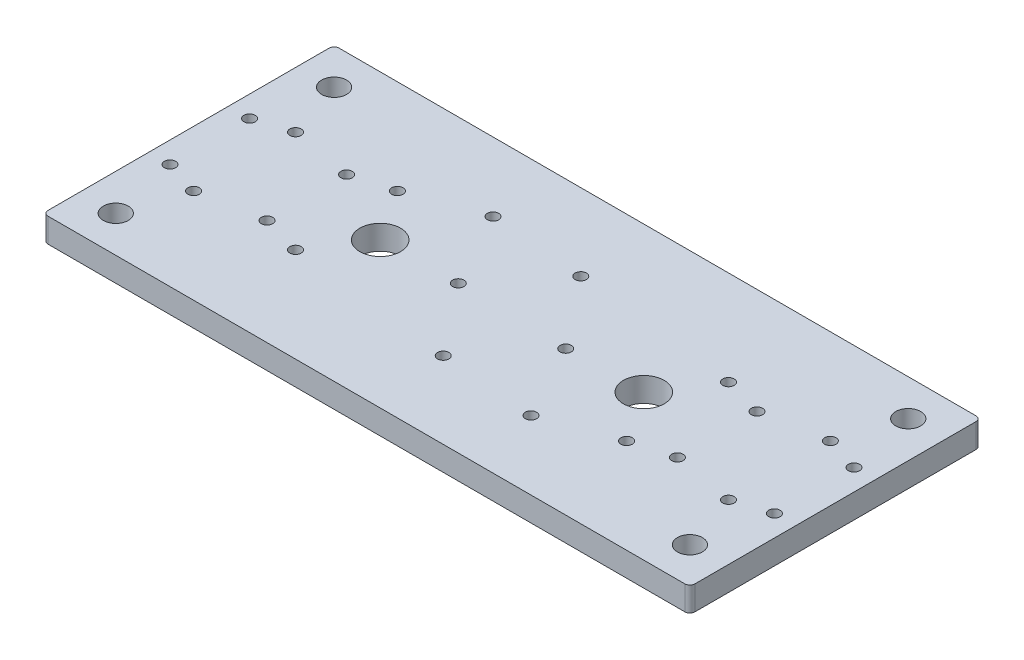
SolidWorks part; units mm, degrees
material "ABS"
ref_plane "Front Plane" through (0, 0, 0) normal (0, 0, 1) x (1, 0, 0)
ref_plane "Top Plane" through (0, 0, 0) normal (0, 1, 0) x (1, 0, 0)
ref_plane "Right Plane" through (0, 0, 0) normal (1, 0, 0) x (0, 0, -1)
sketch "Sketch1" plane through (0, 0, 0) normal (0, 1, 0) x (1, 0, 0)
  line L1 (-127, 57.15) -> (127, 57.15)
  line L2 (-127, 57.15) -> (-127, -57.15)
  line L3 (-127, -57.15) -> (127, -57.15)
  line L4 (127, 57.15) -> (127, -57.15)
  line L5 (-127, 57.15) -> (127, -57.15) construction
  line L6 (-127, -57.15) -> (127, 57.15) construction
  point P0 (0, 0)
  dimension "D1" = 254
  dimension "D2" = 114.3
extrude "Boss-Extrude1" add sketch "Sketch1" along normal blind 9.525 contours L1 L4 L3 L2
sketch "Sketch6" plane through (0, 9.525, 0) normal (0, 1, 0) x (1, 0, 0)
  point P0 (-80.5625, -15.621)
  point P1 (-80.5625, 15.621)
  point P3 (-118.6625, -15.621)
  point P5 (-118.6625, 15.621)
  point P7 (118.6625, -15.621)
  point P9 (80.5625, -15.621)
  point P11 (80.5625, 15.621)
  point P13 (118.6625, 15.621)
hole_wizard "M3 Clearance Hole1" positions "Sketch6" profile "Sketch7" hole size "M3" standard "ANSI Metric"
sketch "Sketch7" plane through (-80.5625, 9.525, 15.621) normal (1, 0, 0) x (0, 0, 1)
  line L0 (0, 0) -> (0, 11.3369)
  line L1 (0, 11.3369) -> (2.225, 10)
  line L2 (2.225, 10) -> (2.225, 0)
  line L5 (2.225, 0) -> (0, 0)
  line L10 (0, 11.3369) -> (-2.225, 10) construction
  line L11 (0, -6.35) -> (0, 107.95) construction
  dimension "Hole Dia." = 4.45
  dimension "Hole Depth" = 10
  dimension "Drill Angle" = 118
sketch "Sketch8" plane through (0, 0, 0) normal (0, -1, 0) x (1, 0, 0)
  line L0 (127, 0) -> (-127, 0) construction
  line L1 (127, -57.15) -> (127, 57.15) construction
  line L2 (-127, -57.15) -> (-127, 57.15) construction
  line L3 (0, 57.15) -> (0, -57.15) construction
  line L4 (-127, 57.15) -> (127, 57.15) construction
  line L5 (-127, -57.15) -> (127, -57.15) construction
  point P0 (112.7125, 42.8625)
  point P13 (112.7125, -42.8625)
  point P14 (-112.7125, -42.8625)
  point P15 (-112.7125, 42.8625)
  dimension "D1" = 14.2875
  dimension "D2" = 14.2875
hole_wizard "3/8 Clearance Hole1" positions "Sketch9" profile "Sketch10" hole size "3/8" standard "ANSI Inch"
sketch "Sketch9" plane through (0, 0, 0) normal (0, -1, 0) x (-1, 0, 0)
  point P0 (-112.7125, 42.8625)
  point P3 (-112.7125, -42.8625)
  point P6 (112.7125, -42.8625)
  point P9 (112.7125, 42.8625)
sketch "Sketch10" plane through (112.7125, 0, -42.8625) normal (1, 0, 0) x (0, 0, -1)
  line L0 (0, 0) -> (0, 12.9455)
  line L1 (0, 12.9455) -> (4.9022, 10)
  line L2 (4.9022, 10) -> (4.9022, 0)
  line L5 (4.9022, 0) -> (0, 0)
  line L10 (0, 12.9455) -> (-4.9022, 10) construction
  line L11 (0, -6.35) -> (0, 107.95) construction
  dimension "Hole Dia." = 9.8044
  dimension "Hole Depth" = 10
  dimension "Drill Angle" = 118
sketch "Sketch11" plane through (0, 0, 0) normal (0, -1, 0) x (1, 0, 0)
  line L0 (0, 57.15) -> (0, -57.15) construction
  line L1 (-127, 57.15) -> (127, 57.15) construction
  line L2 (-127, -57.15) -> (127, -57.15) construction
  line L3 (127, 0) -> (-127, 0) construction
  line L4 (127, -57.15) -> (127, 57.15) construction
  line L5 (-127, -57.15) -> (-127, 57.15) construction
  line L7 (105, 20) -> (65, 20) construction
  line L8 (105, 20) -> (105, -20) construction
  line L9 (105, -20) -> (65, -20) construction
  line L10 (65, 20) -> (65, -20) construction
  line L11 (105, 20) -> (65, -20) construction
  line L12 (105, -20) -> (65, 20) construction
  point P12 (85, 0)
  point P13 (65, -20)
  point P14 (105, 20)
  point P15 (105, -20)
  point P16 (65, 20)
  point P17 (-65, -20)
  point P18 (-65, 20)
  point P19 (-105, 20)
  point P20 (-105, -20)
  point P27 (65, 20)
  point P33 (65, -20)
  point P35 (105, -20)
  point P37 (105, 20)
  dimension "D1" = 40
  dimension "D2" = 40
  dimension "D3" = 65
hole_wizard "M3 Clearance Hole2" positions "Sketch11" profile "Sketch12" hole size "M3" standard "ANSI Metric"
sketch "Sketch12" plane through (105, 0, 20) normal (1, 0, 0) x (0, 0, -1)
  line L0 (0, 0) -> (0, 11.3369)
  line L1 (0, 11.3369) -> (2.225, 10)
  line L2 (2.225, 10) -> (2.225, 0)
  line L5 (2.225, 0) -> (0, 0)
  line L10 (0, 11.3369) -> (-2.225, 10) construction
  line L11 (0, -6.35) -> (0, 107.95) construction
  dimension "Hole Dia." = 4.45
  dimension "Hole Depth" = 10
  dimension "Drill Angle" = 118
fillet "Fillet1" radius 2 4 edges at (127, 4.7625, 57.15) (127, 4.7625, -57.15) (-127, 4.7625, 57.15) (-127, 4.7625, -57.15)
sketch "Sketch16" plane through (0, 0, 0) normal (0, -1, 0) x (1, 0, 0)
  line L0 (0, -57.15) -> (0, 57.15) construction
  line L1 (-125, -57.15) -> (125, -57.15) construction
  line L2 (-125, 57.15) -> (125, 57.15) construction
  line L4 (-40.15, -37) -> (-19.05, -37) construction
  line L5 (-40.15, -37) -> (-40.15, 6.35) construction
  line L6 (-40.15, 6.35) -> (-19.05, 6.35) construction
  line L7 (-19.05, -37) -> (-19.05, 6.35) construction
  line L9 (19.05, -6.35) -> (40.15, -6.35) construction
  line L10 (19.05, -6.35) -> (19.05, 37) construction
  line L11 (19.05, 37) -> (40.15, 37) construction
  line L12 (40.15, -6.35) -> (40.15, 37) construction
  line L13 (19.05, -6.35) -> (40.15, 37) construction
  line L14 (19.05, 37) -> (40.15, -6.35) construction
  line L16 (-10.95, -27.15) -> (10.95, -27.15) construction
  line L17 (-10.95, -27.15) -> (-10.95, 27.15) construction
  line L18 (-10.95, 27.15) -> (10.95, 27.15) construction
  line L19 (10.95, -27.15) -> (10.95, 27.15) construction
  line L20 (-10.95, -27.15) -> (10.95, 27.15) construction
  line L21 (-10.95, 27.15) -> (10.95, -27.15) construction
  point P11 (-21.65, -0.55)
  point P12 (-37.55, -30.1)
  point P57 (37.55, 30.1)
  point P59 (21.65, 0.55)
  point P93 (0, 27)
  point P96 (0, -27)
  point P100 (-10.95, 0)
  dimension "D1" = 43.35
  dimension "D2" = 21.1
  dimension "D3" = 19.05
  dimension "D4" = 2.6
  dimension "D5" = 36.45
  dimension "D6" = 2.6
  dimension "D7" = 36.45
  dimension "D8" = 21.1
  dimension "D9" = 43.35
  dimension "D10" = 50.8
  dimension "D11" = 19.05
  dimension "D12" = 2.6
  dimension "D13" = 36.45
  dimension "D14" = 50.8
  dimension "D15" = 2.6
  dimension "D16" = 36.45
  dimension "D17" = 54.3
  dimension "D18" = 21.9
  dimension "D19" = 27.15
  dimension "D20" = 10.95
  dimension "D21" = 27
  dimension "D22" = 27
hole_wizard "M3 Clearance Hole4" positions "Sketch16" profile "Sketch17" hole size "M3" standard "ANSI Metric"
sketch "Sketch17" plane through (0, 0, -27) normal (1, 0, 0) x (0, 0, -1)
  line L0 (0, 0) -> (0, 11.3369)
  line L1 (0, 11.3369) -> (2.225, 10)
  line L2 (2.225, 10) -> (2.225, 0)
  line L5 (2.225, 0) -> (0, 0)
  line L10 (0, 11.3369) -> (-2.225, 10) construction
  line L11 (0, -6.35) -> (0, 107.95) construction
  dimension "Hole Dia." = 4.45
  dimension "Hole Depth" = 10
  dimension "Drill Angle" = 118
sketch "Sketch18" plane through (0, 0, 0) normal (0, -1, 0) x (1, 0, 0)
  line L0 (127, 0) -> (-127, 0) construction
  line L1 (0, 57.15) -> (0, -57.15) construction
  line L2 (-125, 57.15) -> (125, 57.15) construction
  line L3 (-125, -57.15) -> (125, -57.15) construction
  circle A0 centre (-51.75, 0) radius 8
  circle A1 centre (51.75, 0) radius 8
  dimension "D1" = 16
  dimension "D2" = 51.75
extrude "Cut-Extrude1" cut sketch "Sketch18" against normal through all
